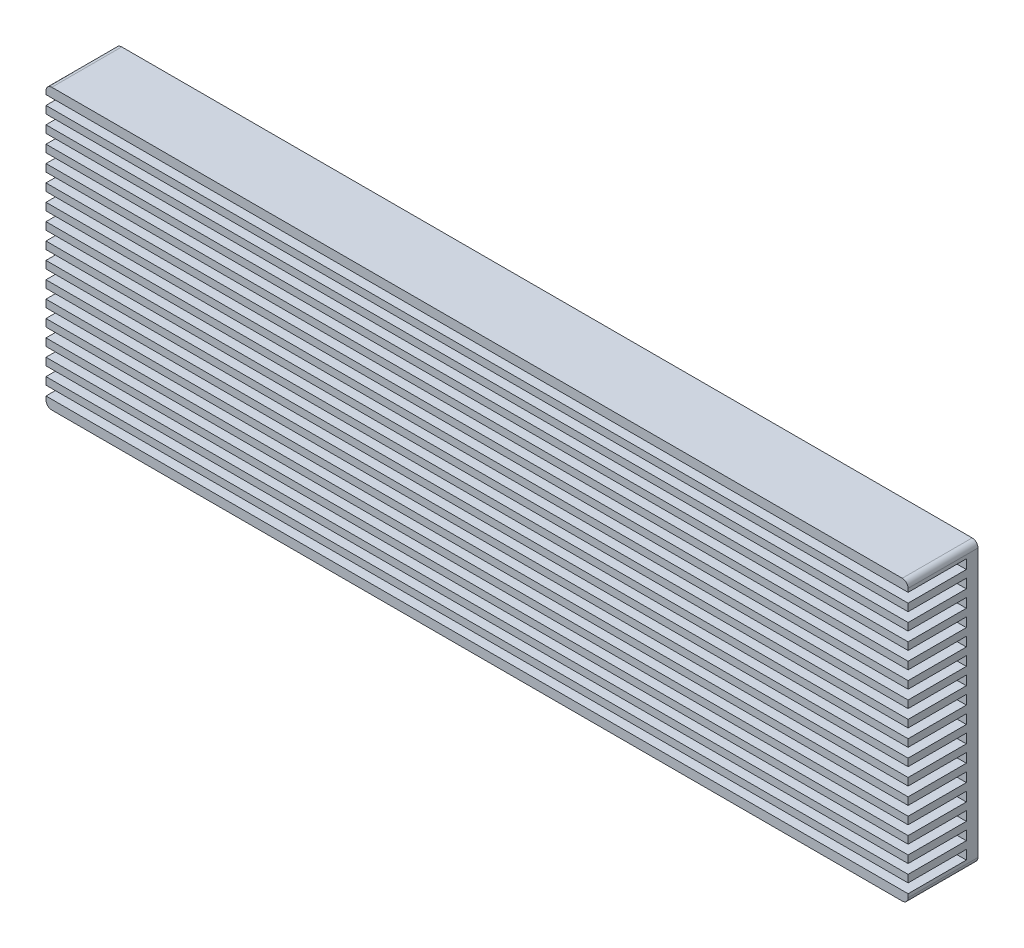
SolidWorks part; units mm, degrees
ref_plane "前视基准面" through (0, 0, 0) normal (0, 0, 1) x (1, 0, 0)
ref_plane "上视基准面" through (0, 0, 0) normal (0, 1, 0) x (1, 0, 0)
ref_plane "右视基准面" through (0, 0, 0) normal (1, 0, 0) x (0, 0, -1)
sketch "草图1" plane through (0, 0, 0) normal (0, 0, 1) x (1, 0, 0)
  line L1 (0, 0) -> (74, 0)
  line L2 (0, 0) -> (0, -24)
  line L3 (0, -24) -> (74, -24)
  line L4 (74, 0) -> (74, -24)
extrude "凸台-拉伸1" add sketch "草图1" along normal blind 6
sketch "草图2" plane through (0, 0, 6) normal (0, 0, 1) x (1, 0, 0)
  line L0 (0, 0) -> (0, -24) construction
  line L1 (0, -23.2) -> (74, -23.2)
  line L2 (0, -23.2) -> (0, -22.4)
  line L3 (0, -22.4) -> (74, -22.4)
  line L4 (74, -23.2) -> (74, -22.4)
  line L5 (74, -24) -> (74, 0) construction
  line L6 (0, -24) -> (74, -24) construction
  line L7 (0, -21.76) -> (74, -21.76)
  line L8 (0, -21.76) -> (0, -20.96)
  line L9 (0, -20.96) -> (74, -20.96)
  line L10 (74, -21.76) -> (74, -20.96)
  line L11 (0, -20.32) -> (74, -20.32)
  line L12 (0, -20.32) -> (0, -19.52)
  line L13 (0, -19.52) -> (74, -19.52)
  line L14 (74, -20.32) -> (74, -19.52)
  line L15 (0, -18.88) -> (74, -18.88)
  line L16 (0, -18.88) -> (0, -18.08)
  line L17 (0, -18.08) -> (74, -18.08)
  line L18 (74, -18.88) -> (74, -18.08)
  line L19 (0, -17.44) -> (74, -17.44)
  line L20 (0, -17.44) -> (0, -16.64)
  line L21 (0, -16.64) -> (74, -16.64)
  line L22 (74, -17.44) -> (74, -16.64)
  line L23 (0, -16) -> (74, -16)
  line L24 (0, -16) -> (0, -15.2)
  line L25 (0, -15.2) -> (74, -15.2)
  line L26 (74, -16) -> (74, -15.2)
  line L27 (0, -14.56) -> (74, -14.56)
  line L28 (0, -14.56) -> (0, -13.76)
  line L29 (0, -13.76) -> (74, -13.76)
  line L30 (74, -14.56) -> (74, -13.76)
  line L31 (0, -13.12) -> (74, -13.12)
  line L32 (0, -13.12) -> (0, -12.32)
  line L33 (0, -12.32) -> (74, -12.32)
  line L34 (74, -13.12) -> (74, -12.32)
  line L35 (0, -11.68) -> (74, -11.68)
  line L36 (0, -11.68) -> (0, -10.88)
  line L37 (0, -10.88) -> (74, -10.88)
  line L38 (74, -11.68) -> (74, -10.88)
  line L39 (0, -10.24) -> (74, -10.24)
  line L40 (0, -10.24) -> (0, -9.44)
  line L41 (0, -9.44) -> (74, -9.44)
  line L42 (74, -10.24) -> (74, -9.44)
  line L43 (0, -8.8) -> (74, -8.8)
  line L44 (0, -8.8) -> (0, -8)
  line L45 (0, -8) -> (74, -8)
  line L46 (74, -8.8) -> (74, -8)
  line L47 (0, -7.36) -> (74, -7.36)
  line L48 (0, -7.36) -> (0, -6.56)
  line L49 (0, -6.56) -> (74, -6.56)
  line L50 (74, -7.36) -> (74, -6.56)
  line L51 (0, -5.92) -> (74, -5.92)
  line L52 (0, -5.92) -> (0, -5.12)
  line L53 (0, -5.12) -> (74, -5.12)
  line L54 (74, -5.92) -> (74, -5.12)
  line L55 (0, -4.48) -> (74, -4.48)
  line L56 (0, -4.48) -> (0, -3.68)
  line L57 (0, -3.68) -> (74, -3.68)
  line L58 (74, -4.48) -> (74, -3.68)
  line L59 (0, -3.04) -> (74, -3.04)
  line L60 (0, -3.04) -> (0, -2.24)
  line L61 (0, -2.24) -> (74, -2.24)
  line L62 (74, -3.04) -> (74, -2.24)
  line L63 (0, -1.6) -> (74, -1.6)
  line L64 (0, -1.6) -> (0, -0.8)
  line L65 (0, -0.8) -> (74, -0.8)
  line L66 (74, -1.6) -> (74, -0.8)
  dimension "D1" = 0.8
  dimension "D2" = 0.8
  dimension "D3" = 16
extrude "切除-拉伸1" cut sketch "草图2" against normal blind 5
fillet "圆角1" radius 0.5 4 edges at (74, -24, 3) (0, -24, 3) (0, 0, 3) (74, 0, 3)
